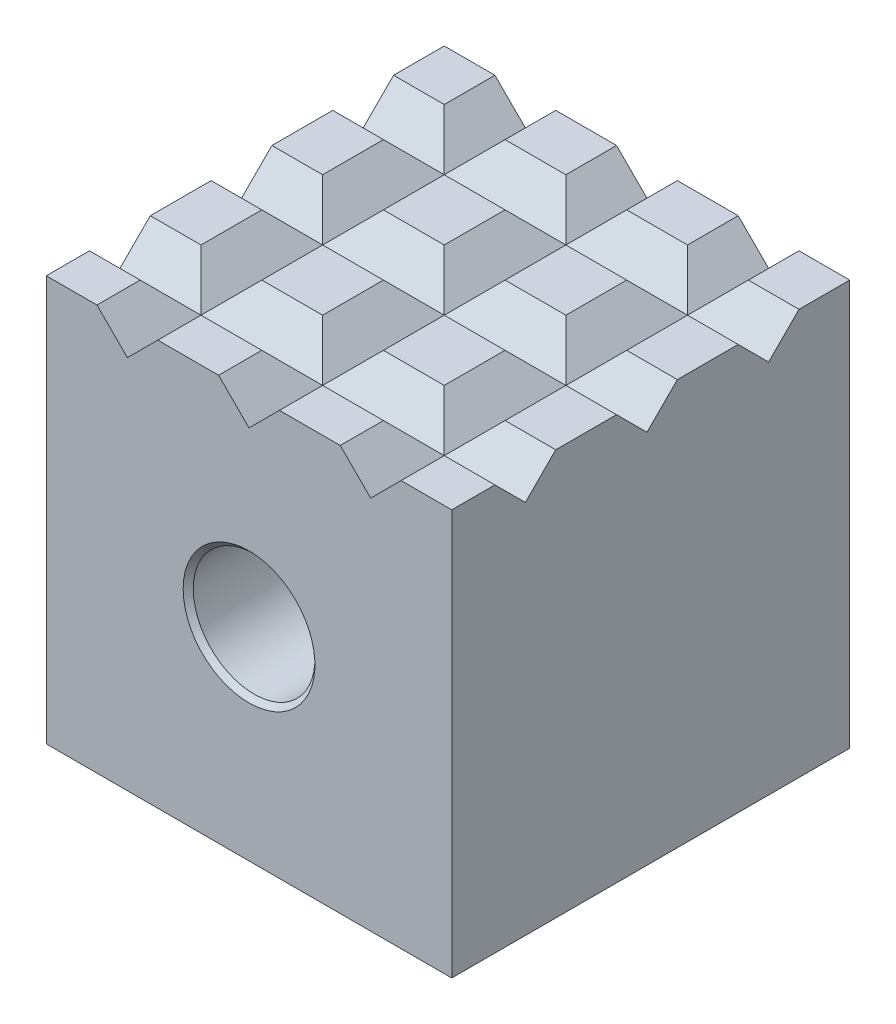
SolidWorks part; units mm, degrees
ref_plane "Front Plane" through (0, 0, 0) normal (0, 0, 1) x (1, 0, 0)
ref_plane "Top Plane" through (0, 0, 0) normal (0, 1, 0) x (1, 0, 0)
ref_plane "Right Plane" through (0, 0, 0) normal (1, 0, 0) x (0, 0, -1)
sketch "Sketch1" plane through (0, 0, 0) normal (0, 0, 1) x (1, 0, 0)
  line L1 (-10, -10) -> (10, -10)
  line L2 (-10, -10) -> (-10, 10)
  line L3 (-10, 10) -> (10, 10)
  line L4 (10, -10) -> (10, 10)
  line L5 (-10, -10) -> (10, 10) construction
  line L6 (-10, 10) -> (10, -10) construction
  circle A0 centre (0, 0) radius 3
  point P0 (0, 0)
  dimension "D3" = 6
  dimension "D1" = 20
  dimension "D2" = 20
extrude "Boss-Extrude1" add sketch "Sketch1" along normal blind 19.63
sketch "Sketch2" plane through (0, 0, 0) normal (0, 0, -1) x (-1, 0, 0)
  line L0 (0, 0) -> (0, 50000) construction
  line L1 (0, 8.5) -> (-1.5, 10)
  line L2 (-10, 10) -> (10, 10) construction
  line L3 (-1.5, 10) -> (-4.5, 10)
  line L4 (-4.5, 10) -> (-6, 8.5)
  line L5 (-6, 8.5) -> (-6, 10.4951) construction
  line L6 (6, 8.5) -> (6, 10.4951) construction
  line L7 (1.5, 10) -> (4.5, 10)
  line L8 (4.5, 10) -> (6, 8.5)
  line L9 (0, 8.5) -> (1.5, 10)
  line L10 (-10.5, 10) -> (-7.5, 10)
  line L11 (-12, 8.5) -> (-10.5, 10)
  line L12 (-7.5, 10) -> (-6, 8.5)
  line L13 (7.5, 10) -> (6, 8.5)
  line L14 (12, 8.5) -> (10.5, 10)
  line L15 (10.5, 10) -> (7.5, 10)
  line L16 (-7.5, 10) -> (7.5, 10)
  line M7 (10, 10) -> (-10, 10)
  dimension "D1" = 6
  dimension "D2" = 45
  dimension "D3" = 45
  dimension "D4" = 0
  dimension "D5" = 1.5
extrude "Cut-Extrude1" cut sketch "Sketch2" against normal blind 26 contours L12 L4 M7 | L1 L9 M7 | L13 L8 M7
sketch "Sketch3" plane through (-10, 0, 10) normal (1, 0, 0) x (0, 0, -1)
  line L0 (0, 0) -> (0, 50000) construction
  line L1 (0, 8.5) -> (-1.5, 10)
  line L3 (-1.5, 10) -> (-4.5, 10)
  line L4 (-4.5, 10) -> (-6, 8.5)
  line L5 (-6, 8.5) -> (-6, 10.4951) construction
  line L6 (6, 8.5) -> (6, 10.4951) construction
  line L7 (1.5, 10) -> (4.5, 10)
  line L8 (4.5, 10) -> (6, 8.5)
  line L9 (0, 8.5) -> (1.5, 10)
  line L10 (-10.5, 10) -> (-7.5, 10)
  line L11 (-12, 8.5) -> (-10.5, 10)
  line L12 (-7.5, 10) -> (-6, 8.5)
  line L13 (7.5, 10) -> (6, 8.5)
  line L14 (12, 8.5) -> (10.5, 10)
  line L15 (10.5, 10) -> (7.5, 10)
  line L16 (-7.5, 10) -> (7.5, 10)
  line M26 (-9.63, 10) -> (10, 10)
extrude "Cut-Extrude2" cut sketch "Sketch3" along normal blind 26 contours L13 L8 M26 | L9 L1 M26 | L12 L4 M26
chamfer "Chamfer1" distance 0.25 angle 45 1 edges at (3, 0, 0)
chamfer "Chamfer2" distance 0.25 angle 45 1 edges at (3, 0, 19.63)
